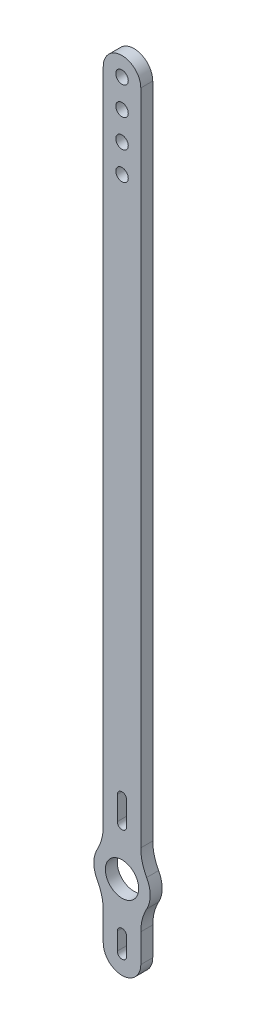
SolidWorks part; units mm, degrees
ref_plane "Front Plane" through (0, 0, 0) normal (0, 0, 1) x (1, 0, 0)
ref_plane "Top Plane" through (0, 0, 0) normal (0, 1, 0) x (1, 0, 0)
ref_plane "Right Plane" through (0, 0, 0) normal (1, 0, 0) x (0, 0, -1)
sketch "Model" plane through (0, 0, 0) normal (0, 0, 1) x (1, 0, 0)
  line L0 (-1, 18.4215) -> (-1, -3.4062) construction
  line L1 (1, 18.4215) -> (1, 5.9161) construction
  line L7 (-7.5978, 10.1) -> (4.5933, 10.1) construction
  line L8 (-1.9126, -10.1) -> (1, -10.1) construction
  line L9 (-3.5953, 15.1) -> (3.0222, 15.1) construction
  line L10 (-2.3019, -13.8) -> (3.0222, -13.8) construction
  line L11 (-4, 148) -> (-4, 7.746)
  line L12 (4, 148) -> (4, 7.746)
  line L13 (-1, -10.1) -> (-1, -13.8)
  line L14 (1, -10.1) -> (1, -13.8)
  line L15 (-1, 15.1) -> (-1, 10.1)
  line L16 (1, 15.1) -> (1, 10.1)
  line L17 (1, 3.4062) -> (1, -5.9161) construction
  line L18 (1, -10.1) -> (1, -18.7667) construction
  line L19 (-1, -5.9161) -> (-1, -18.7667) construction
  line L20 (-4, -7.746) -> (-4, -13.8)
  line L21 (4, -7.746) -> (4, -13.8)
  circle A0 centre (0, 0) radius 3.55
  arc A1 (-5.25, 2.9047) -> (-5.25, -2.9047) centre (0, 0) ccw
  arc A2 (1, 15.1) -> (-1, 15.1) centre (0, 15.1) ccw
  arc A3 (-1, 10.1) -> (1, 10.1) centre (0, 10.1) ccw
  arc A4 (1, -10.1) -> (-1, -10.1) centre (0, -10.1) ccw
  arc A5 (-1, -13.8) -> (1, -13.8) centre (0, -13.8) ccw
  arc A7 (4, 148) -> (-4, 148) centre (0, 148) ccw
  arc A8 (-4, -13.8) -> (4, -13.8) centre (0, -13.8) ccw
  arc A9 (5.25, -2.9047) -> (5.25, 2.9047) centre (0, 0) ccw
  arc A10 (4, 7.746) -> (5.25, 2.9047) centre (14, 7.746) ccw
  arc A11 (5.25, -2.9047) -> (4, -7.746) centre (14, -7.746) ccw
  arc A12 (-5.25, -2.9047) -> (-4, -7.746) centre (-14, -7.746) cw
  arc A13 (-5.25, 2.9047) -> (-4, 7.746) centre (-14, 7.746) ccw
  circle A14 centre (0, 148) radius 1.33
  circle A15 centre (0, 142) radius 1.33
  circle A16 centre (0, 136) radius 1.33
  circle A17 centre (0, 130) radius 1.33
  point P44 (4, -4.4721)
  point P47 (-4, -4.4721)
  dimension "D1" = 7.1
  dimension "D2" = 12
  dimension "D5" = 10
  dimension "D7" = 2.66
  dimension "D8" = 2.66
  dimension "D20" = 2.66
  dimension "D21" = 2.66
  dimension "D3" = 1
  dimension "D4" = 1
  dimension "D6" = 0
  dimension "D9" = 10.1
  dimension "D10" = 10.1
  dimension "D11" = 3.7
  dimension "D12" = 5
  dimension "D13" = 4
  dimension "D14" = 4
  dimension "D16" = 148
  dimension "D17" = 6
  dimension "D18" = 6
  dimension "D19" = 6
  dimension "D22" = 130
extrude "Boss-Extrude1" add sketch "Model" along normal blind 2.55
